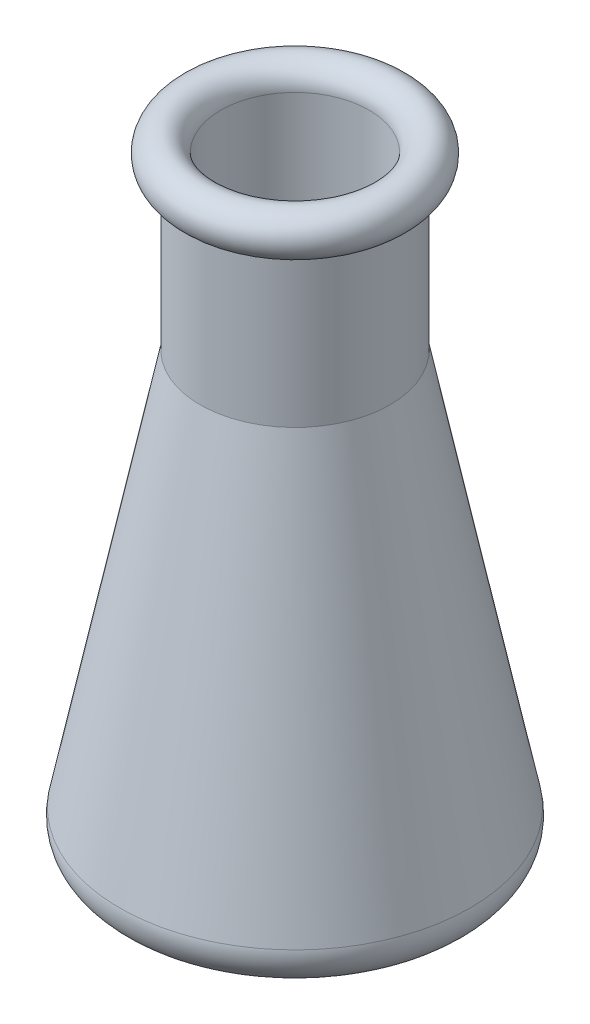
SolidWorks part; units mm, degrees
ref_plane "Płaszczyzna przednia" through (0, 0, 0) normal (0, 0, 1) x (1, 0, 0)
ref_plane "Płaszczyzna górna" through (0, 0, 0) normal (0, 1, 0) x (1, 0, 0)
ref_plane "Płaszczyzna prawa" through (0, 0, 0) normal (1, 0, 0) x (0, 0, -1)
sketch "Sketch1" plane through (0, 0, 0) normal (0, 0, 1) x (1, 0, 0)
  line L1 (8.9, -2.188) -> (8.9, -27.3801)
  line L2 (11.4, -4.688) -> (11.4, -22.688)
  line L3 (0, -75) -> (22, -75)
  line L4 (0, -27.3801) -> (0, -75)
  line L5 (11.4, -22.688) -> (22, -75)
  line L6 (8.9, -27.3801) -> (0, -27.3801)
  arc A0 (12.6094, 0) -> (11.4, -4.688) centre (11.4, -2.188) cw
  arc A1 (11.4, -4.688) -> (8.9, -2.188) centre (11.4, -2.188) ccw
  dimension "D2" = 2.5
  dimension "D1" = 11.4
  dimension "D3" = 18
  dimension "D4" = 22
revolve "Revolve1" add sketch "Sketch1" angle 360 about L4
fillet "Fillet1" radius 4 1 edges at (-22, -75, 0)
